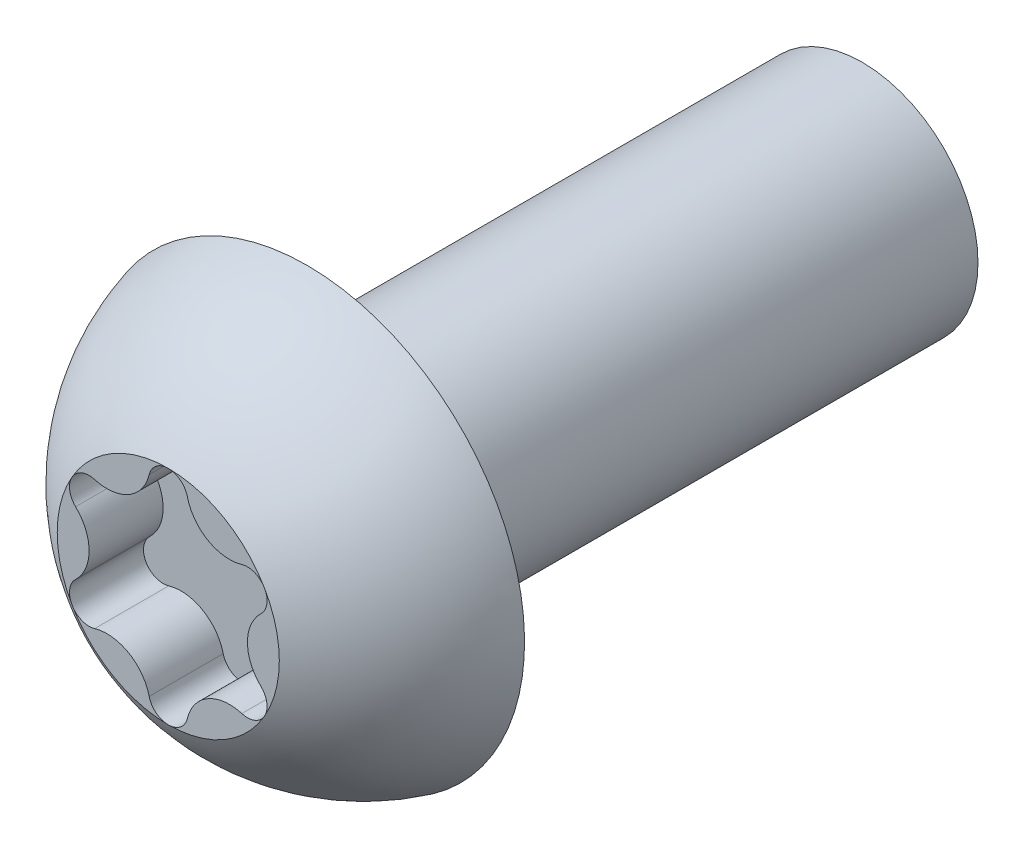
SolidWorks part; units mm, degrees
material "AISI Type A2 Tool Steel"
ref_plane "Face" through (0, 0, 0) normal (0, 0, 1) x (1, 0, 0)
ref_plane "Dessus" through (0, 0, 0) normal (0, 1, 0) x (1, 0, 0)
ref_plane "Droite" through (0, 0, 0) normal (1, 0, 0) x (0, 0, -1)
sketch "Esquisse1" plane through (0, 0, 0) normal (1, 0, 0) x (0, 0, -1)
  line L0 (-1.5, 0) -> (-1.5, 1.2)
  line L1 (0, 2.35) -> (0, 1.25)
  line L2 (0, 1.25) -> (6, 1.25)
  line L3 (6, 1.25) -> (6, 0)
  line L4 (6, 0) -> (-1.5, 0)
  line L5 (-1.5, 0) -> (-18.0711, 0) construction
  arc A0 (-1.5, 1.2) -> (0, 2.35) centre (0.6108, 0) cw
  dimension "M" = 2.5
  dimension "DH" = 4.7
  dimension "A" = 2.4
  dimension "K" = 1.5
  dimension "L" = 6
revolve "Révolution1" add sketch "Esquisse1" angle 360 about L5
cosmetic thread "Représentation de filetage1" [suppressed] parameters "D2"=1.548
cosmetic thread "Représentation de filetage2" parameters "D2"=1.993
cosmetic thread "Représentation de filetage3" [suppressed] parameters "D2"=2.439
cosmetic thread "Représentation de filetage4" [suppressed] parameters "D2"=3.22
cosmetic thread "Représentation de filetage5" [suppressed] parameters "D2"=4.11
cosmetic thread "Représentation de filetage6" [suppressed] parameters "D2"=4.891
cosmetic thread "Représentation de filetage7" [suppressed] parameters "D2"=6.891
sketch "Esquisse2" plane through (0, 0, 1.5) normal (0, 0, 1) x (1, 0, 0)
  line L0 (0, 1.8503) -> (0, -1.9994) construction
  line L1 (-2.0152, 0) -> (2.4489, 0) construction
  line L2 (0, 0) -> (-0.3794, 1.9074) construction
  line L3 (0, 0) -> (0.3821, 1.9207) construction
  line L4 (0, 0) -> (1.3768, 1.2074) construction
  line L5 (0, 0) -> (1.8862, 1.089) construction
  line L6 (0, 0.9878) -> (-0.8555, 0.4939) construction
  line L7 (-0.8555, 0.4939) -> (-0.8555, -0.4939) construction
  line L8 (-0.8555, -0.4939) -> (0, -0.9878) construction
  line L9 (0, -0.9878) -> (0.8555, -0.4939) construction
  line L10 (0.8555, -0.4939) -> (0.8555, 0.4939) construction
  line L11 (0.8555, 0.4939) -> (0, 0.9878) construction
  circle A0 centre (0, 0) radius 1.2 construction
  circle A1 centre (0, 0) radius 1.2 construction
  arc A2 (-0.2063, 1.0373) -> (0.2063, 1.0373) centre (0, 0.9878) cw
  arc A3 (0.2063, 1.0373) -> (0.7952, 0.6974) centre (0.6621, 1.1467) ccw
  circle A4 centre (0, 0) radius 0.8555 construction
  arc A5 (0.7952, 0.6974) -> (1.0015, 0.34) centre (0.8555, 0.4939) cw
  arc A6 (1.0015, 0.34) -> (1.0015, -0.34) centre (1.3241, 0) ccw
  arc A7 (1.0015, -0.34) -> (0.7952, -0.6974) centre (0.8555, -0.4939) cw
  arc A8 (0.7952, -0.6974) -> (0.2063, -1.0373) centre (0.6621, -1.1467) ccw
  arc A9 (0.2063, -1.0373) -> (-0.2063, -1.0373) centre (0, -0.9878) cw
  arc A10 (-0.2063, -1.0373) -> (-0.7952, -0.6974) centre (-0.6621, -1.1467) ccw
  arc A11 (-0.7952, -0.6974) -> (-1.0015, -0.34) centre (-0.8555, -0.4939) cw
  arc A12 (-1.0015, -0.34) -> (-1.0015, 0.34) centre (-1.3241, 0) ccw
  arc A13 (-1.0015, 0.34) -> (-0.7952, 0.6974) centre (-0.8555, 0.4939) cw
  arc A14 (-0.7952, 0.6974) -> (-0.2063, 1.0373) centre (-0.6621, 1.1467) ccw
  point P0 (0.4277, 0.7408)
  point P14 (0, 1.2)
  dimension "D1" = 22.5
  dimension "D2" = 11.25
  dimension "D3" = 6
extrude "Enlèv. mat.-Extru.1" cut sketch "Esquisse2" against normal blind 0.8
equation "\"D2@Esquisse2\" = \"D1@Esquisse2\"/2"
